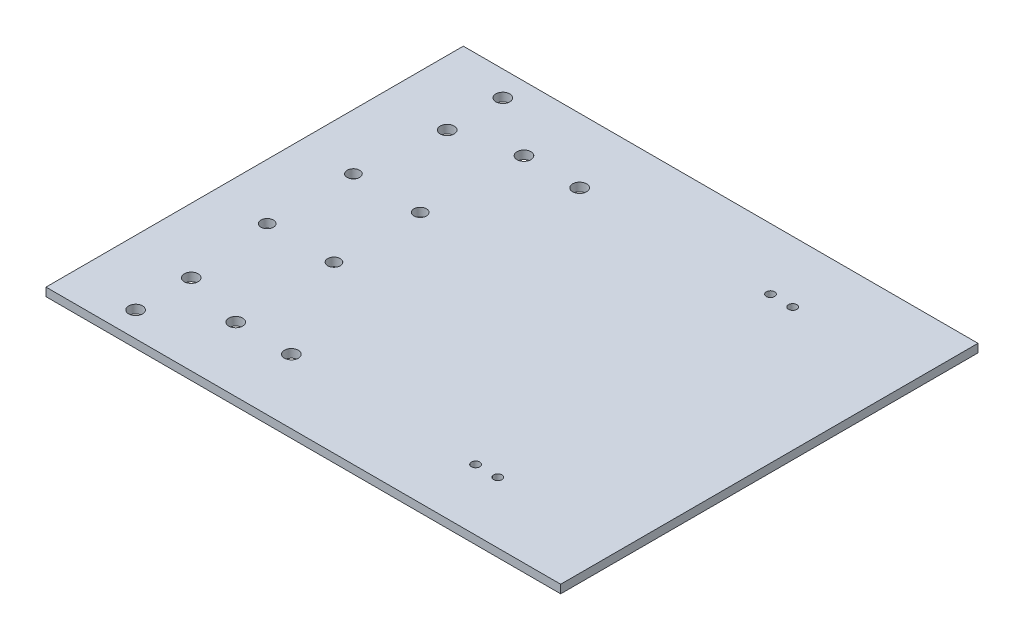
SolidWorks part; units mm, degrees
ref_plane "Front Plane" through (0, 0, 0) normal (0, 0, 1) x (1, 0, 0)
ref_plane "Top Plane" through (0, 0, 0) normal (0, 1, 0) x (1, 0, 0)
ref_plane "Right Plane" through (0, 0, 0) normal (1, 0, 0) x (0, 0, -1)
sketch "Sketch2" plane through (0, 0, 0) normal (0, 1, 0) x (1, 0, 0)
  line L1 (0, 0) -> (185, 0)
  line L2 (0, 0) -> (0, 150)
  line L3 (0, 150) -> (185, 150)
  line L4 (185, 0) -> (185, 150)
  dimension "D1" = 185
  dimension "D2" = 150
extrude "Boss-Extrude1" add sketch "Sketch2" along normal blind 3
sketch "Sketch3" plane through (0, 3, 0) normal (0, 1, 0) x (1, 0, 0)
  line L0 (0, 150) -> (0, 0) construction
  line L1 (185, 0) -> (185, 150) construction
  line L2 (92.5, 150) -> (92.5, 0) construction
  line L3 (185, 150) -> (0, 150) construction
  line L4 (0, 0) -> (185, 0) construction
  line L5 (0, 75) -> (185, 75) construction
  line L6 (0, 150) -> (0, 0) construction
  line L7 (185, 0) -> (185, 150) construction
  line L8 (0, 0) -> (185, 0) construction
  line L9 (185, 150) -> (0, 150) construction
  circle A9 centre (140.4, 128) radius 1.5
  circle A10 centre (132.4, 128) radius 1.5
  circle A11 centre (132.4, 22) radius 1.5
  circle A12 centre (140.4, 22) radius 1.5
  circle A13 centre (20, 90.5) radius 2.25
  circle A14 centre (44, 90.5) radius 2.25
  circle A15 centre (44, 59.5) radius 2.25
  circle A16 centre (20, 59.5) radius 2.25
  circle A17 centre (45, 23.2) radius 2.5
  circle A18 centre (65, 23.2) radius 2.5
  circle A19 centre (65, 126.8) radius 2.5
  circle A20 centre (45, 126.8) radius 2.5
  circle A21 centre (23.2, 9) radius 2.5
  circle A22 centre (23.2, 29) radius 2.5
  circle A23 centre (23.2, 121) radius 2.5
  circle A24 centre (23.2, 141) radius 2.5
  point P48 (25.5111, 18.6403)
  dimension "D1" = 3
  dimension "D2" = 44.6
  dimension "D3" = 22
  dimension "D4" = 3
  dimension "D5" = 22
  dimension "D6" = 8
  dimension "D7" = 4.5
  dimension "D8" = 4.5
  dimension "D9" = 24
  dimension "D10" = 15.5
  dimension "D11" = 15.5
  dimension "D12" = 20
  dimension "D13" = 20
  dimension "D14" = 23.2
  dimension "D15" = 23.2
  dimension "D16" = 5
  dimension "D17" = 5
  dimension "D18" = 45
  dimension "D19" = 9
  dimension "D20" = 23.2
  dimension "D21" = 5
  dimension "D22" = 5
  dimension "D23" = 20
  dimension "D24" = 23.2
extrude "Cut-Extrude1" cut sketch "Sketch3" against normal blind 10
